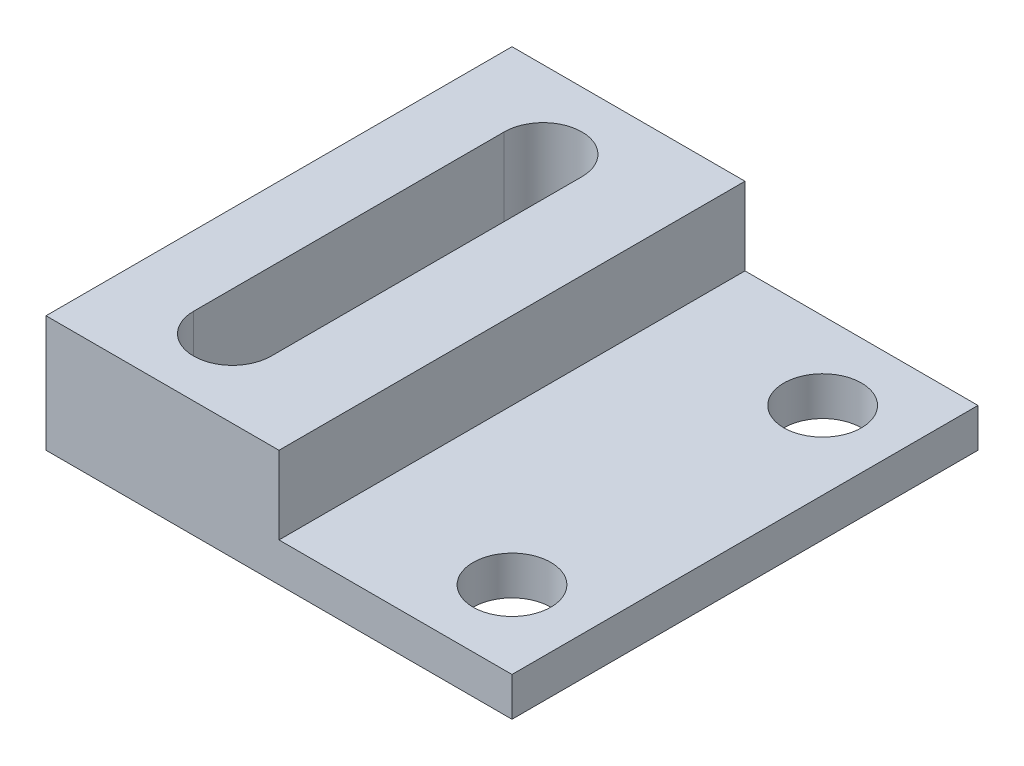
SolidWorks part; units mm, degrees
ref_plane "Front Plane" through (0, 0, 0) normal (0, 0, 1) x (1, 0, 0)
ref_plane "Top Plane" through (0, 0, 0) normal (0, 1, 0) x (1, 0, 0)
ref_plane "Right Plane" through (0, 0, 0) normal (1, 0, 0) x (0, 0, -1)
sketch "Sketch1" plane through (0, 0, 0) normal (0, 0, 1) x (1, 0, 0)
  line L1 (-19.05, -4.7625) -> (19.05, -4.7625)
  line L2 (-19.05, -4.7625) -> (-19.05, 4.7625)
  line L3 (-19.05, 4.7625) -> (19.05, 4.7625)
  line L4 (19.05, -4.7625) -> (19.05, 4.7625)
  line L5 (-19.05, -4.7625) -> (19.05, 4.7625) construction
  line L6 (-19.05, 4.7625) -> (19.05, -4.7625) construction
  point P0 (0, 0)
  dimension "D1" = 38.1
  dimension "D2" = 9.525
extrude "Boss-Extrude1" add sketch "Sketch1" along normal mid plane 38.1
sketch "Sketch2" plane through (0, 0, 19.05) normal (0, 0, 1) x (1, 0, 0)
  line L0 (0, -5.2388) -> (0, 5.2388) construction
  line L1 (0, -1.5875) -> (19.05, -1.5875)
  line L2 (0, -1.5875) -> (0, 4.7625)
  line L3 (0, 4.7625) -> (19.05, 4.7625)
  line L4 (19.05, -1.5875) -> (19.05, 4.7625)
  point P6 (0, 0)
  dimension "D1" = 6.35
extrude "Cut-Extrude1" cut sketch "Sketch2" against normal through all
sketch "Sketch3" plane through (0, -1.5875, 0) normal (0, 1, 0) x (1, 0, 0)
  line L1 (0, -5.2388) -> (0, 5.2388) construction
  line L2 (12.7, 12.7) -> (12.7, -12.7) construction
  line L3 (-5.2388, 0) -> (5.2388, 0) construction
  point P0 (12.7, 12.7)
  point P1 (12.7, -12.7)
  point P2 (5.6667, 12.7)
  point P8 (12.7, 0)
  dimension "D1" = 25.4
  dimension "D3" = 12.7
hole_wizard "1/4 (0.25) Diameter Hole2" positions "Sketch9" profile "Sketch10" hole size "1/4" standard "ANSI Inch" end condition through all
sketch "Sketch9" plane through (0, -1.5875, 0) normal (0, 1, 0) x (1, 0, 0)
  point P0 (12.7, 12.7)
  point P3 (12.7, -12.7)
sketch "Sketch10" plane through (12.7, -1.5875, -12.7) normal (1, 0, 0) x (0, 0, 1)
  line L0 (0, 0) -> (0, 3.175)
  line L1 (0, 3.175) -> (3.175, 3.175)
  line L2 (3.175, 3.175) -> (3.175, 0)
  line L5 (3.175, 0) -> (0, 0)
  line L11 (0, -6.35) -> (0, 107.95) construction
  dimension "Thru Hole Dia." = 6.35
  dimension "Thru Hole Depth" = 3.175
sketch "Sketch11" plane through (0, 4.7625, 0) normal (0, 1, 0) x (1, 0, 0)
  line L0 (-10.16, -12.7) -> (-10.16, 12.7) construction
  line L1 (-13.335, -12.7) -> (-13.335, 12.7)
  line L2 (-6.985, -12.7) -> (-6.985, 12.7)
  line L3 (-5.2388, 0) -> (5.2388, 0) construction
  line L4 (0, -5.2388) -> (0, 5.2388) construction
  arc A0 (-13.335, -12.7) -> (-6.985, -12.7) centre (-10.16, -12.7) ccw
  arc A1 (-6.985, 12.7) -> (-13.335, 12.7) centre (-10.16, 12.7) ccw
  point P2 (-10.16, 0)
  point P7 (0, 0)
  dimension "D1" = 6.35
  dimension "D2" = 25.4
  dimension "D3" = 10.16
extrude "Cut-Extrude2" cut sketch "Sketch11" against normal blind 31.75
